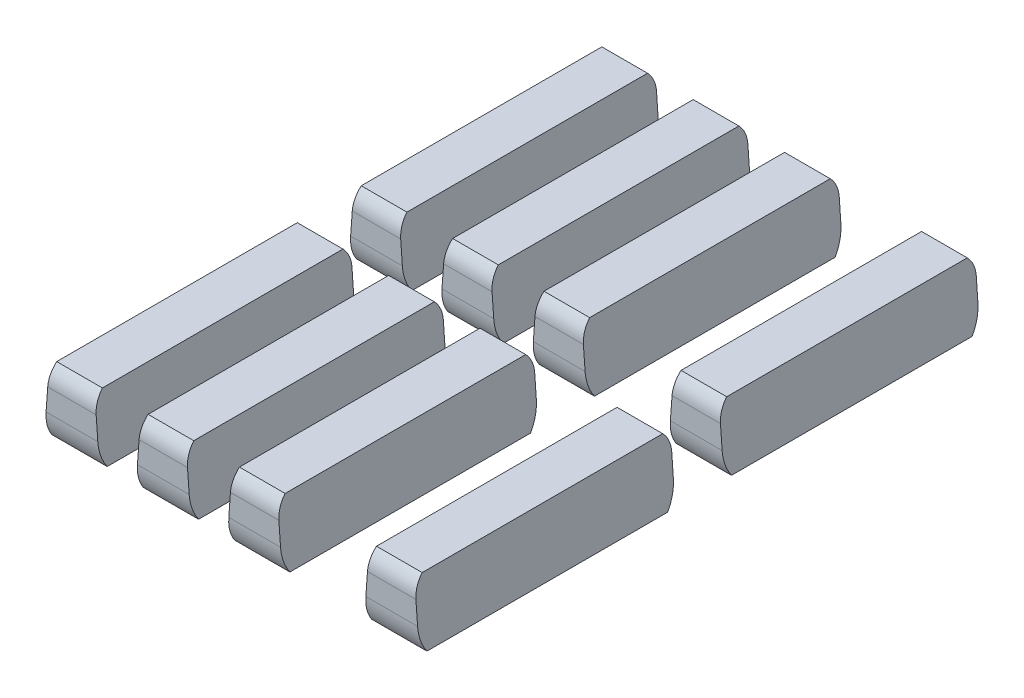
SolidWorks part; units mm, degrees
ref_plane "Front Plane" through (0, 0, 0) normal (0, 0, 1) x (1, 0, 0)
ref_plane "Top Plane" through (0, 0, 0) normal (0, 1, 0) x (1, 0, 0)
ref_plane "Right Plane" through (0, 0, 0) normal (1, 0, 0) x (0, 0, -1)
sketch "Sketch1" plane through (0, 0, 0) normal (0, 1, 0) x (1, 0, 0)
  line L0 (9.1562, 0.75) -> (9.1562, 20.75) construction
  line L1 (-10, 20.75) -> (28.3124, 20.75)
  line L2 (-10, 20.75) -> (-10, -19.25)
  line L3 (-10, -19.25) -> (28.3124, -19.25)
  line L4 (28.3124, 20.75) -> (28.3124, -19.25)
  line L5 (9.1562, 0.75) -> (28.3124, 0.75) construction
  line L6 (-10, 20.75) -> (28.3124, 20.75) construction
sketch "Sketch2" plane through (0, 0, 0) normal (0, 0, 1) x (1, 0, 0)
  line L24 (1.6562, -2.344) -> (1.8141, -4.5) construction
  line L25 (0.1562, -2.344) -> (1.6562, -2.344) construction
  line L26 (-0.0017, -4.5) -> (0.1562, -2.344) construction
  line L27 (1.8141, -4.5) -> (-0.0017, -4.5) construction
  line L28 (3.1562, -2.344) -> (2.9983, -4.5) construction
  line L29 (4.6562, -2.344) -> (3.1562, -2.344) construction
  line L30 (4.8141, -4.5) -> (4.6562, -2.344) construction
  line L31 (2.9983, -4.5) -> (4.8141, -4.5) construction
  line L32 (5.9983, -4.5) -> (6.1562, -2.344) construction
  line L33 (6.1562, -2.344) -> (7.6562, -2.344) construction
  line L34 (7.6562, -2.344) -> (7.8141, -4.5) construction
  line L35 (7.8141, -4.5) -> (5.9983, -4.5) construction
  line L36 (10.6562, -2.344) -> (9.1562, -2.344) construction
  line L37 (9.1562, -2.344) -> (8.9983, -4.5) construction
  line L38 (8.9983, -4.5) -> (10.8141, -4.5) construction
  line L39 (10.8141, -4.5) -> (10.6562, -2.344) construction
  line L40 (12.1562, -2.344) -> (13.6562, -2.344) construction
  line L41 (13.6562, -2.344) -> (13.8141, -4.5) construction
  line L42 (13.8141, -4.5) -> (11.9983, -4.5) construction
  line L43 (11.9983, -4.5) -> (12.1562, -2.344) construction
  line L44 (18.1562, -2.344) -> (16.6562, -2.344) construction
  line L45 (16.6562, -2.344) -> (16.4983, -4.5) construction
  line L46 (16.4983, -4.5) -> (18.3141, -4.5) construction
  line L47 (18.3141, -4.5) -> (18.1562, -2.344) construction
  line L48 (1.6562, -2.344) -> (1.8141, -4.5) construction
  line L49 (0.1562, -2.344) -> (1.6562, -2.344) construction
  line L50 (-0.0017, -4.5) -> (0.1562, -2.344) construction
  line L51 (1.8141, -4.5) -> (-0.0017, -4.5) construction
  line L52 (3.1562, -2.344) -> (2.9983, -4.5) construction
  line L53 (4.6562, -2.344) -> (3.1562, -2.344) construction
  line L54 (4.8141, -4.5) -> (4.6562, -2.344) construction
  line L55 (2.9983, -4.5) -> (4.8141, -4.5) construction
  line L56 (5.9983, -4.5) -> (6.1562, -2.344)
  line L57 (6.1562, -2.344) -> (7.6562, -2.344)
  line L58 (7.6562, -2.344) -> (7.8141, -4.5)
  line L59 (7.8141, -4.5) -> (5.9983, -4.5)
  line L60 (10.6562, -2.344) -> (9.1562, -2.344)
  line L61 (9.1562, -2.344) -> (8.9983, -4.5)
  line L62 (8.9983, -4.5) -> (10.8141, -4.5)
  line L63 (10.8141, -4.5) -> (10.6562, -2.344)
  line L64 (12.1562, -2.344) -> (13.6562, -2.344)
  line L65 (13.6562, -2.344) -> (13.8141, -4.5)
  line L66 (13.8141, -4.5) -> (11.9983, -4.5)
  line L67 (11.9983, -4.5) -> (12.1562, -2.344)
  line L68 (18.1562, -2.344) -> (16.6562, -2.344)
  line L69 (16.6562, -2.344) -> (16.4983, -4.5)
  line L70 (16.4983, -4.5) -> (18.3141, -4.5)
  line L71 (18.3141, -4.5) -> (18.1562, -2.344)
sketch "Sketch3" plane through (0, 0, 0) normal (1, 0, 0) x (0, 0, -1)
  line L0 (-8.95, -4.5) -> (-11.05, -4.5)
  line L1 (-1.05, -4.5) -> (1.05, -4.5)
  line L2 (8.95, -4.5) -> (11.05, -4.5)
  line L4 (-0.8, -3.7) -> (-0.8, -2.9607) construction
  line L5 (0.8, -3.7) -> (0.8, -2.9607) construction
  line L6 (9.2, -3.7) -> (9.2, -2.9607) construction
  line L7 (-9.2, -3.7) -> (-9.2, -2.9607) construction
  line L8 (-0.8, -3.7) -> (-0.8, -2.9607)
  line L9 (0.8, -3.7) -> (0.8, -2.9607)
  line L10 (9.2, -3.7) -> (9.2, -2.9607)
  line L11 (-9.2, -3.7) -> (-9.2, -2.9607)
  line L12 (-11.05, -2.344) -> (-11.05, -4.5)
  line L13 (11.05, -2.344) -> (11.05, -4.5)
  line L14 (-1.05, -2.344) -> (1.05, -2.344)
  line L16 (8.95, -2.344) -> (11.05, -2.344)
  line L18 (-8.95, -2.344) -> (-11.05, -2.344)
  arc A5 (0.8, -3.7) -> (1.05, -4.5) centre (2.205, -3.7) ccw construction
  arc A7 (-0.8, -2.9607) -> (-1.05, -2.344) centre (-1.6857, -2.9607) ccw construction
  arc A8 (1.05, -2.344) -> (0.8, -2.9607) centre (1.6857, -2.9607) ccw construction
  arc A9 (9.2, -2.9607) -> (8.95, -2.344) centre (8.3143, -2.9607) ccw construction
  arc A10 (-1.05, -4.5) -> (-0.8, -3.7) centre (-2.205, -3.7) ccw construction
  arc A11 (0.8, -3.7) -> (1.05, -4.5) centre (2.205, -3.7) ccw
  arc A13 (8.95, -4.5) -> (9.2, -3.7) centre (7.795, -3.7) ccw construction
  arc A15 (-9.2, -3.7) -> (-8.95, -4.5) centre (-7.795, -3.7) ccw construction
  arc A16 (-1.05, -4.5) -> (-0.8, -3.7) centre (-2.205, -3.7) ccw
  arc A17 (-9.2, -3.7) -> (-8.95, -4.5) centre (-7.795, -3.7) ccw
  arc A18 (8.95, -4.5) -> (9.2, -3.7) centre (7.795, -3.7) ccw
  arc A19 (-8.95, -2.344) -> (-9.2, -2.9607) centre (-8.3143, -2.9607) ccw construction
  arc A20 (-0.8, -2.9607) -> (-1.05, -2.344) centre (-1.6857, -2.9607) ccw
  arc A21 (1.05, -2.344) -> (0.8, -2.9607) centre (1.6857, -2.9607) ccw
  arc A22 (9.2, -2.9607) -> (8.95, -2.344) centre (8.3143, -2.9607) ccw
  arc A23 (-8.95, -2.344) -> (-9.2, -2.9607) centre (-8.3143, -2.9607) ccw
extrude "Boss-Extrude1" add sketch "Sketch2" along normal up to vertex (11.05 mm away) from vertex at -11.05 starting at point (0, -4.5, -11.05)
extrude "Cut-Extrude5" cut sketch "Sketch3" along normal through all from vertex at -0.0017 starting at point (-0.0017, -4.5, 0)
